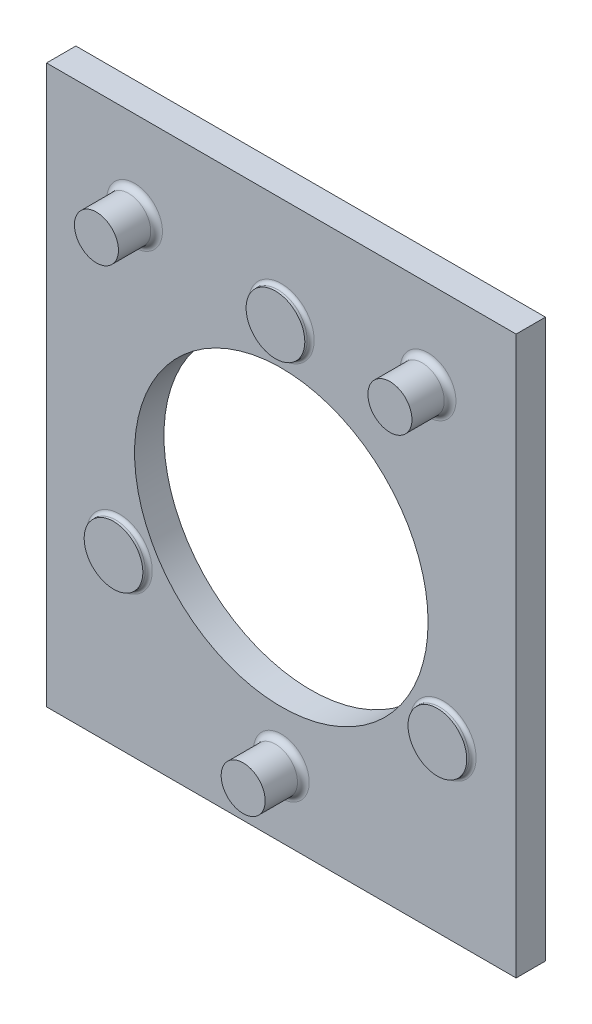
SolidWorks part; units mm, degrees
ref_plane "Front" through (0, 0, 0) normal (0, 0, 1) x (1, 0, 0)
ref_plane "Top" through (0, 0, 0) normal (0, 1, 0) x (1, 0, 0)
ref_plane "Right" through (0, 0, 0) normal (1, 0, 0) x (0, 0, -1)
other "Configuration Table"
sketch "Sketch1" plane through (0, 0, 0) normal (0, 0, 1) x (1, 0, 0)
  line L1 (0, 0) -> (203.2, 0)
  line L2 (0, 0) -> (0, 241.3)
  line L3 (0, 241.3) -> (203.2, 241.3)
  line L4 (203.2, 0) -> (203.2, 241.3)
  circle A0 centre (101.6, 114.3) radius 63.5
  dimension "D3" = 127
  dimension "D1" = 203.2
  dimension "D2" = 241.3
  dimension "D4" = 101.6
  dimension "D5" = 114.3
extrude "Base-Extrude" add sketch "Sketch1" along normal blind 12.7
sketch "Sketch3" plane through (0, 0, 12.7) normal (0, 0, 1) x (1, 0, 0)
  line L0 (101.6, 114.3) -> (101.6, 195.2128) construction
  line L1 (101.6, 114.3) -> (171.6725, 73.8436) construction
  line L2 (101.6, 114.3) -> (31.5275, 73.8436) construction
  circle A0 centre (31.5275, 73.8436) radius 12.7
  circle A1 centre (101.6, 195.2128) radius 12.7
  circle A2 centre (171.6725, 73.8436) radius 12.7
  circle A3 centre (101.6, 114.3) radius 63.5 construction
  circle A4 centre (101.6, 114.3) radius 63.5 construction
  circle A5 centre (101.6, 114.3) radius 80.9128 construction
  dimension "D1" = 25.4
  dimension "D2" = 25.4
  dimension "D3" = 25.4
  dimension "D4" = 161.8256
  dimension "D5" = 120
  dimension "D6" = 120
extrude "Boss-Extrude2" add sketch "Sketch3" along normal blind 2.54
sketch "Sketch4" plane through (0, 0, 12.7) normal (0, 0, 1) x (1, 0, 0)
  line L0 (203.2, 0) -> (203.2, 241.3) construction
  line L1 (203.2, 241.3) -> (0, 241.3) construction
  line L2 (0, 241.3) -> (0, 0) construction
  circle A0 centre (38.1, 203.2) radius 9.525
  circle A1 centre (165.1, 203.2) radius 9.525
  dimension "D1" = 19.05
  dimension "D4" = 19.05
  dimension "D2" = 38.1
  dimension "D3" = 38.1
  dimension "D5" = 38.1
  dimension "D6" = 38.1
extrude "Boss-Extrude4" add sketch "Sketch4" along normal blind 16.51
sketch "Sketch5" plane through (0, 0, 12.7) normal (0, 0, 1) x (1, 0, 0)
  line L0 (101.6, 0) -> (101.6, 52.9028) construction
  line L1 (0, 0) -> (203.2, 0) construction
  circle A1 centre (101.6, 28.575) radius 9.525
  dimension "D1" = 28.575
  dimension "D3" = 19.05
extrude "Boss-Extrude5" add sketch "Sketch5" along normal blind 16.51
fillet "Fillet4" radius 2.54 3 edges at (28.575, 203.2, 12.7) (155.575, 203.2, 12.7) (92.075, 28.575, 12.7)
fillet "Fillet5" radius 1.524 3 edges at (18.8275, 73.8436, 12.7) (88.9, 195.2128, 12.7) (158.9725, 73.8436, 12.7)
